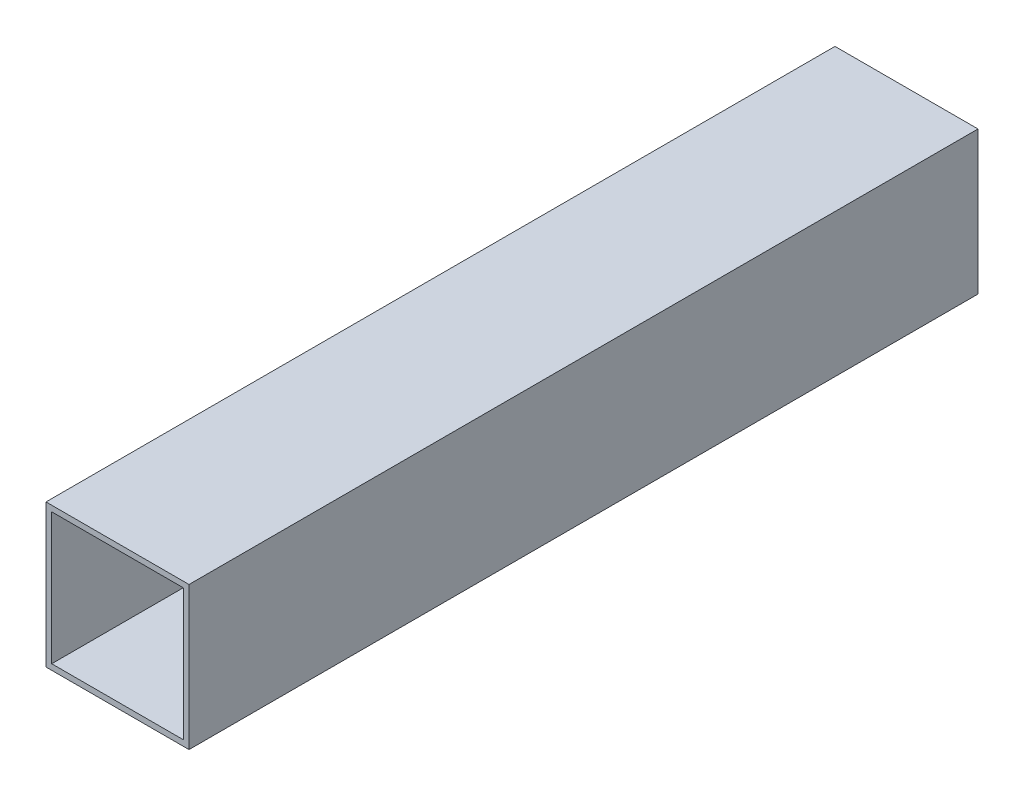
SolidWorks part; units mm, degrees
ref_plane "Front Plane" through (0, 0, 0) normal (0, 0, 1) x (1, 0, 0)
ref_plane "Top Plane" through (0, 0, 0) normal (0, 1, 0) x (1, 0, 0)
ref_plane "Right Plane" through (0, 0, 0) normal (1, 0, 0) x (0, 0, -1)
sketch "Sketch1" plane through (0, 0, 0) normal (0, 0, 1) x (1, 0, 0)
  line L1 (-25, -25) -> (25, -25)
  line L2 (-25, -25) -> (-25, 25)
  line L3 (-25, 25) -> (25, 25)
  line L4 (25, -25) -> (25, 25)
  line L5 (-25, -25) -> (25, 25) construction
  line L6 (-25, 25) -> (25, -25) construction
  line L7 (-23, -23) -> (23, -23)
  line L8 (-23, -23) -> (-23, 23)
  line L9 (-23, 23) -> (23, 23)
  line L10 (23, -23) -> (23, 23)
  line L11 (-23, -23) -> (23, 23) construction
  line L12 (-23, 23) -> (23, -23) construction
  point P0 (0, 0)
  point P6 (0, 0)
  dimension "D1" = 50
  dimension "D2" = 46
extrude "Boss-Extrude1" add sketch "Sketch1" along normal blind 275.86
